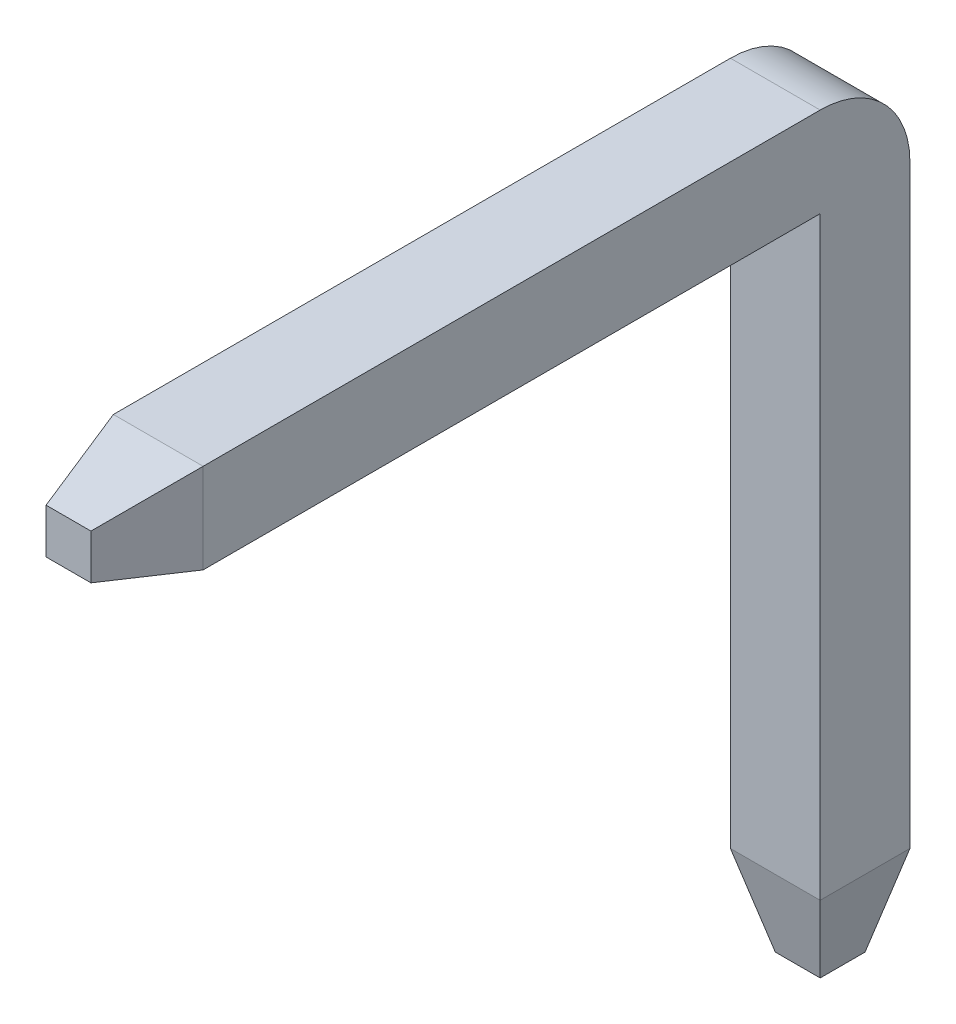
SolidWorks part; units mm, degrees
ref_plane "Спереди" through (0, 0, 0) normal (0, 0, 1) x (1, 0, 0)
ref_plane "Сверху" through (0, 0, 0) normal (0, 1, 0) x (1, 0, 0)
ref_plane "Справа" through (0, 0, 0) normal (1, 0, 0) x (0, 0, -1)
ref_plane "Плоскость1" through (-0.4, 0, 0) normal (-1, 0, 0) x (0, -1, 0)
sketch "Эскиз1" plane through (-0.4, 0, 0) normal (-1, 0, 0) x (0, -1, 0)
  line L0 (3.05, -3.15) -> (-3.85, -3.15)
  line L1 (-3.85, -3.15) -> (-3.85, -3.95)
  line L2 (-3.85, -3.95) -> (3.05, -3.95)
  line L3 (3.05, -3.95) -> (3.05, -3.15)
extrude "Бобышка-Вытянуть1" add sketch "Эскиз1" against normal blind 0.8
sketch "Эскиз2" plane through (0, 0, -3.15) normal (0, 0, 1) x (1, 0, 0)
  line L0 (0.4, 3.05) -> (-0.4, 3.05)
  line L1 (-0.4, 3.05) -> (-0.4, 3.85)
  line L2 (-0.4, 3.85) -> (0.4, 3.85)
  line L3 (0.4, 3.85) -> (0.4, 3.05)
extrude "Бобышка-Вытянуть2" add sketch "Эскиз2" along normal blind 6.3
chamfer "Фаска1" distance 0.2 angle 75.964 4 edges at (0, -3.05, -3.15) (0.4, -3.05, -3.55) (-0.4, -3.05, -3.55) (0, -3.05, -3.95)
chamfer "Фаска2" distance 0.2 angle 75.964 4 edges at (0, 3.85, 3.15) (0.4, 3.45, 3.15) (-0.4, 3.45, 3.15) (0, 3.05, 3.15)
fillet "Скругление1" radius 0.8 1 edges at (0, 3.85, -3.95)
